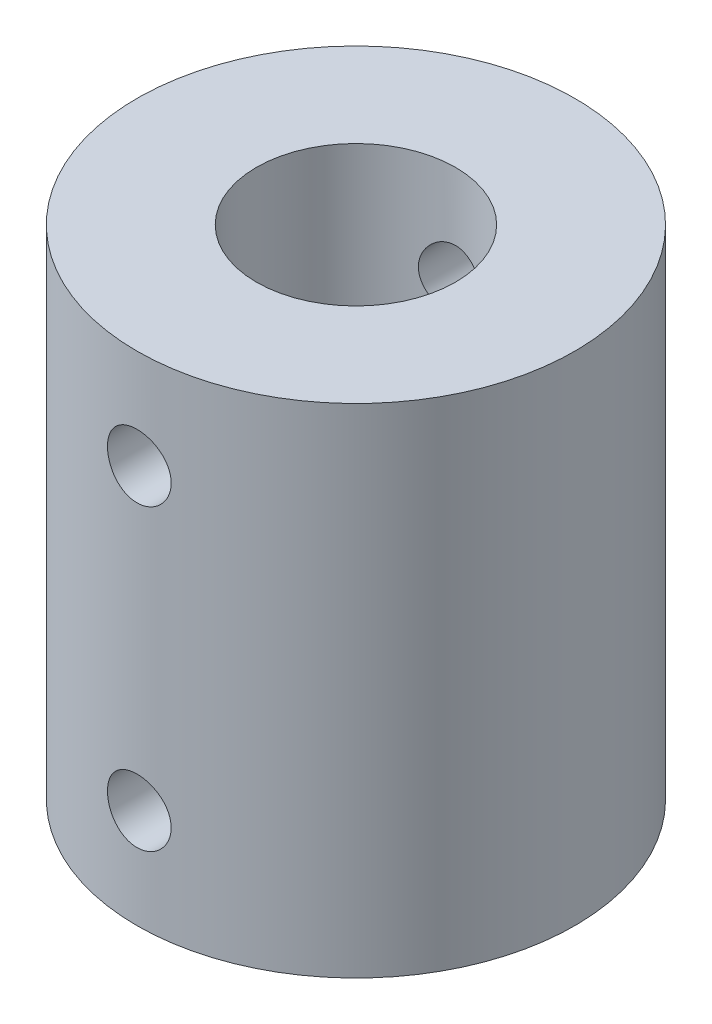
SolidWorks part; units mm, degrees
ref_plane "正面" through (0, 0, 0) normal (0, 0, 1) x (1, 0, 0)
ref_plane "平面" through (0, 0, 0) normal (0, 1, 0) x (1, 0, 0)
ref_plane "右側面" through (0, 0, 0) normal (1, 0, 0) x (0, 0, -1)
sketch "ｽｹｯﾁ1" plane through (0, 0, 0) normal (0, 1, 0) x (1, 0, 0)
  circle A0 centre (0, 0) radius 11
  circle A1 centre (0, 0) radius 5
  dimension "D1" = 22
  dimension "D2" = 10
extrude "ﾎﾞｽ - 押し出し1" add sketch "ｽｹｯﾁ1" along normal mid plane 25
sketch "ｽｹｯﾁ2" plane through (0, 0, 0) normal (0, 0, 1) x (1, 0, 0)
  line L0 (0, 0) -> (0, 7.5) construction
  line L1 (0, 0) -> (11, 0) construction
  line L2 (11, -12.5) -> (11, 12.5) construction
  circle A0 centre (0, 7.5) radius 1.6
  circle A1 centre (0, -7.5) radius 1.6
  dimension "D2" = 3.2
  dimension "D1" = 7.5
extrude "ｶｯﾄ - 押し出し1" cut sketch "ｽｹｯﾁ2" against normal mid plane 25
